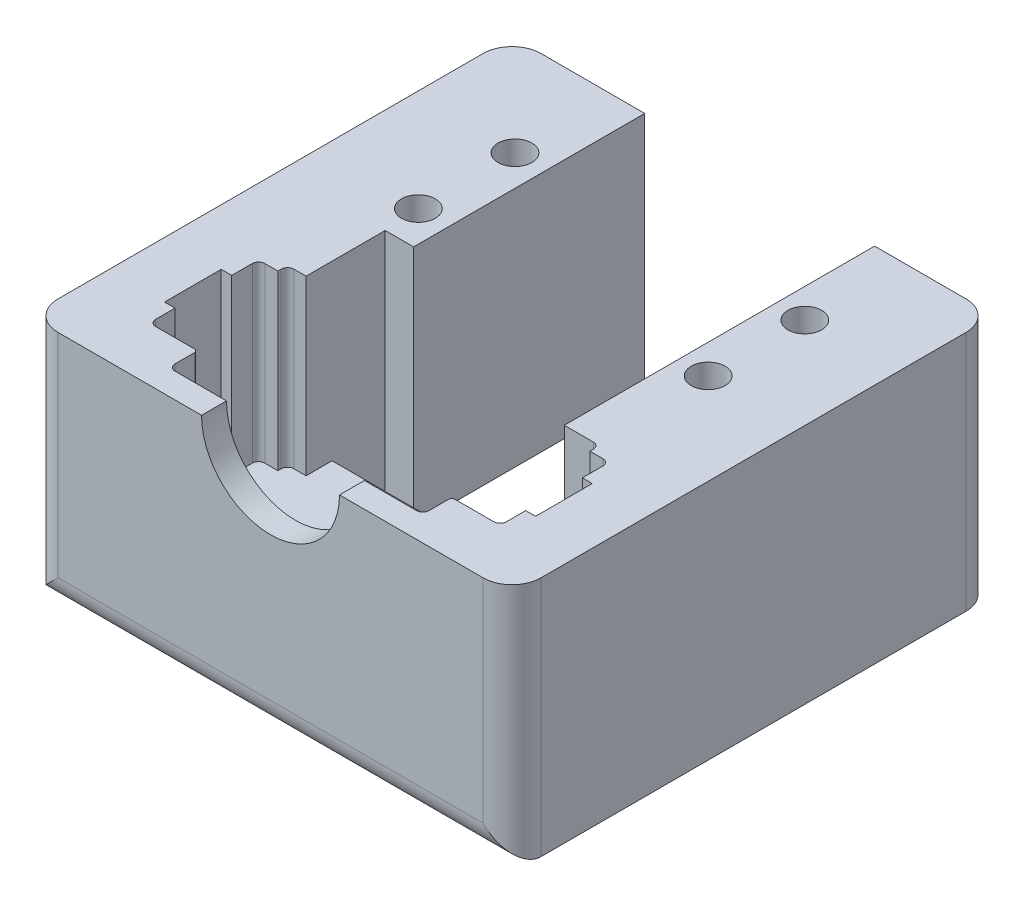
SolidWorks part; units mm, degrees
ref_plane "前视基准面" through (0, 0, 0) normal (0, 0, 1) x (1, 0, 0)
ref_plane "上视基准面" through (0, 0, 0) normal (0, 1, 0) x (1, 0, 0)
ref_plane "右视基准面" through (0, 0, 0) normal (1, 0, 0) x (0, 0, -1)
sketch "草图1" plane through (0, 0, 0) normal (0, 1, 0) x (1, 0, 0)
  line L1 (-25, -25) -> (25, -25)
  line L2 (-25, -25) -> (-25, 25)
  line L3 (-25, 25) -> (-11.2619, 25)
  line L4 (25, -25) -> (25, 25)
  line L5 (-6.2707, -6.2707) -> (25, 25) construction
  line L6 (-25, 25) -> (0, 0) construction
  line L7 (-18.1805, -10.8988) -> (-19.2049, -10.8988)
  line L10 (-15.4695, -7.1202) -> (-14.2003, -7.1202)
  line L11 (16.1805, -7.7702) -> (16.1805, -8.1202)
  line L12 (16.1805, -8.1202) -> (17.5305, -8.1202)
  line L13 (18.1805, -8.7702) -> (18.1805, -10.8988)
  line L14 (17.5305, -19.4202) -> (13.5305, -19.4202)
  line L24 (13.1805, -21.7702) -> (13.1805, -19.7702)
  line L25 (12.5305, -22.4202) -> (-12.4695, -22.4202)
  line L26 (-13.1195, -21.7702) -> (-13.1195, -19.7702)
  line L27 (-13.4695, -19.4202) -> (-17.4695, -19.4202)
  line L28 (-18.1195, -18.7702) -> (-18.1195, -16.7665)
  line L29 (-17.4695, -8.1202) -> (-16.1195, -8.1202)
  line L30 (-16.1195, -7.7702) -> (-16.1195, -8.1202)
  line L31 (18.1805, -10.8988) -> (19.2049, -10.8988)
  line L32 (19.2049, -10.8988) -> (19.2049, -16.7665)
  line L33 (19.2049, -16.7665) -> (18.1805, -16.7665)
  line L35 (0, -35.6784) -> (0, 5.6108) construction
  line L36 (-19.2049, -10.8988) -> (-19.2049, -16.7665)
  line L37 (-19.2049, -16.7665) -> (-18.1805, -16.7665)
  line L39 (-18.1805, -10.8988) -> (-18.1195, -10.8988)
  line L40 (-18.1805, -16.7665) -> (-18.1195, -16.7665)
  line L41 (18.1805, -16.7665) -> (18.1805, -18.7702)
  line L42 (-18.1195, -10.8988) -> (-18.1195, -8.7702)
  line L43 (-11.2619, 25) -> (-11.2619, 1.0711)
  line L44 (-11.2619, 1.0711) -> (-14.2003, 1.0711)
  line L45 (-14.2003, 1.0711) -> (-14.2003, -7.1202)
  line L47 (12.5305, -7.1202) -> (12.5305, 25)
  line L49 (7.1202, -7.1202) -> (25, -25) construction
  line L51 (12.5305, -7.1202) -> (15.5305, -7.1202)
  line L52 (12.5305, 25) -> (25, 25)
  arc A2 (16.1805, -7.7702) -> (15.5305, -7.1202) centre (15.5305, -7.7702) ccw
  arc A3 (18.1805, -8.7702) -> (17.5305, -8.1202) centre (17.5305, -8.7702) ccw
  arc A4 (17.5305, -19.4202) -> (18.1805, -18.7702) centre (17.5305, -18.7702) ccw
  arc A5 (13.5305, -19.4202) -> (13.1805, -19.7702) centre (13.5305, -19.7702) ccw
  arc A6 (12.5305, -22.4202) -> (13.1805, -21.7702) centre (12.5305, -21.7702) ccw
  arc A7 (-13.1195, -21.7702) -> (-12.4695, -22.4202) centre (-12.4695, -21.7702) ccw
  arc A8 (-13.1195, -19.7702) -> (-13.4695, -19.4202) centre (-13.4695, -19.7702) ccw
  arc A18 (-18.1195, -18.7702) -> (-17.4695, -19.4202) centre (-17.4695, -18.7702) ccw
  arc A19 (-17.4695, -8.1202) -> (-18.1195, -8.7702) centre (-17.4695, -8.7702) ccw
  arc A20 (-15.4695, -7.1202) -> (-16.1195, -7.7702) centre (-15.4695, -7.7702) ccw
  point P0 (0, 0)
  dimension "D1" = 50
  dimension "D2" = 50
extrude "凸台-拉伸1" add sketch "草图1" along normal blind 25
sketch "草图2" plane through (0, 0, 25) normal (0, 0, 1) x (1, 0, 0)
  line L4 (-25, 0) -> (25, 0)
  line L5 (25, 0) -> (25, 25)
  line L6 (25, 25) -> (-25, 25)
  line L7 (-25, 25) -> (-25, 0)
  line L8 (-25, 0) -> (25, 0)
  line L9 (25, 0) -> (25, 25)
  line L10 (25, 25) -> (-25, 25)
  line L11 (-25, 25) -> (-25, 0)
  arc A0 (-7.139, 25) -> (7.139, 25) centre (0, 25) ccw
  dimension "D1" = 0
extrude "切除-拉伸1" cut sketch "草图2" against normal blind 10 contours L10 A0
sketch "草图5" plane through (0, 0, 0) normal (0, -1, 0) x (1, 0, 0)
  line L1 (-20.889, 4.4234) -> (20.889, 4.4234)
  line L2 (-20.889, 4.4234) -> (-20.889, 23.3182)
  line L3 (-20.889, 23.3182) -> (20.889, 23.3182)
  line L4 (20.889, 4.4234) -> (20.889, 23.3182)
  line L5 (-20.889, 4.4234) -> (20.889, 23.3182) construction
  line L6 (-20.889, 23.3182) -> (20.889, 4.4234) construction
  point P0 (0, 13.8708)
extrude "凸台-拉伸4" add sketch "草图5" against normal blind 7.1
sketch "草图7" plane through (0, 25, 0) normal (0, 1, 0) x (1, 0, 0)
  circle A4 centre (15.551, 4.753) radius 1.75
  circle A5 centre (15.551, 14.753) radius 1.75
  circle A6 centre (-14.449, 4.753) radius 1.75
  circle A7 centre (-14.449, 14.753) radius 1.75
  dimension "D1" = 3.5
  dimension "D2" = 3.5
  dimension "D3" = 3.5
  dimension "D4" = 3.5
extrude "切除-拉伸2" cut sketch "草图7" against normal through all
fillet "圆角1" radius 3 6 edges at (-0.8349, 0, 4.4234) (0, 0, 25) (25, 12.5, -25) (-25, 12.5, -25) (-25, 12.5, 25) (25, 12.5, 25)
